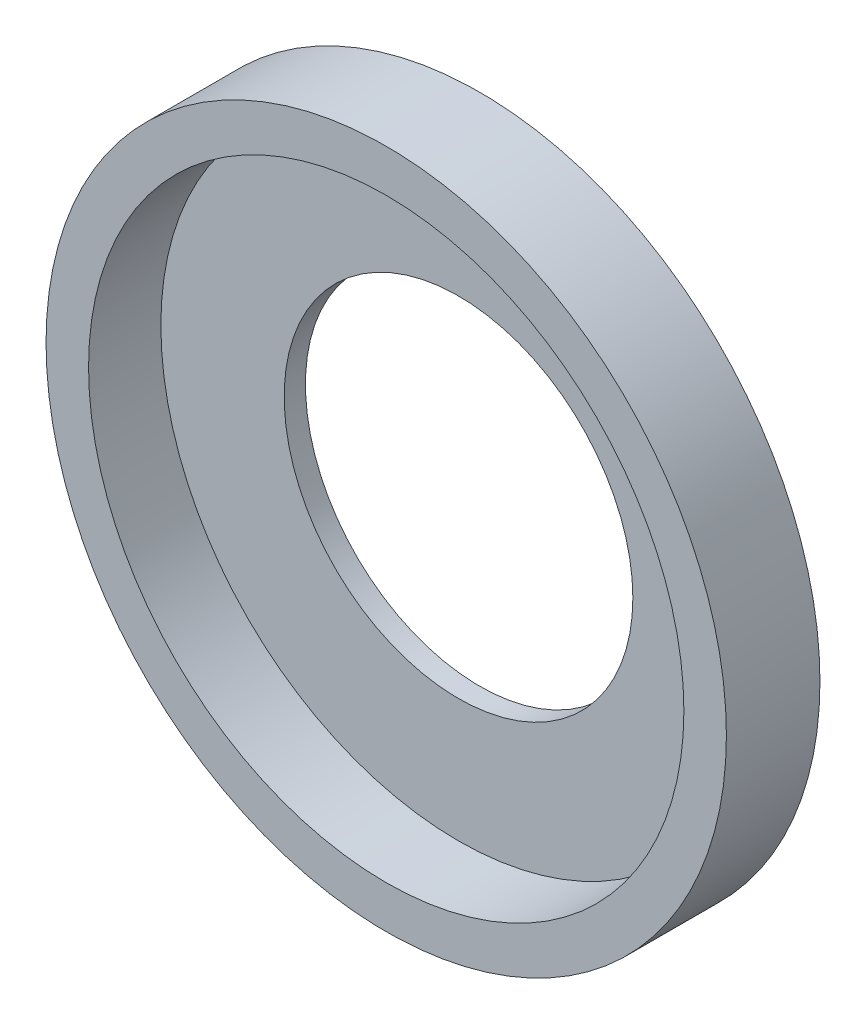
SolidWorks part; units mm, degrees
material "7075-T6 (SN)"
ref_plane "Front Plane" through (0, 0, 0) normal (0, 0, 1) x (1, 0, 0)
ref_plane "Top Plane" through (0, 0, 0) normal (0, 1, 0) x (1, 0, 0)
ref_plane "Right Plane" through (0, 0, 0) normal (1, 0, 0) x (0, 0, -1)
sketch "Sketch1" plane through (0, 0, 0) normal (0, 0, 1) x (1, 0, 0)
  circle A0 centre (0, 0) radius 8
  circle A1 centre (0, 0) radius 4.1
extrude "Outer_Flange_Contact_Annulus_ID8p2" add sketch "Sketch1" along normal blind 0.5 from offset 3.5
sketch "Sketch2" plane through (0, 0, 0) normal (0, 0, 1) x (1, 0, 0)
  circle A0 centre (0, 0) radius 8
  circle A1 centre (0, 0) radius 7
extrude "M14x0p5_Internal_Thread_Envelope" add sketch "Sketch2" along normal blind 1.7 from offset 3
